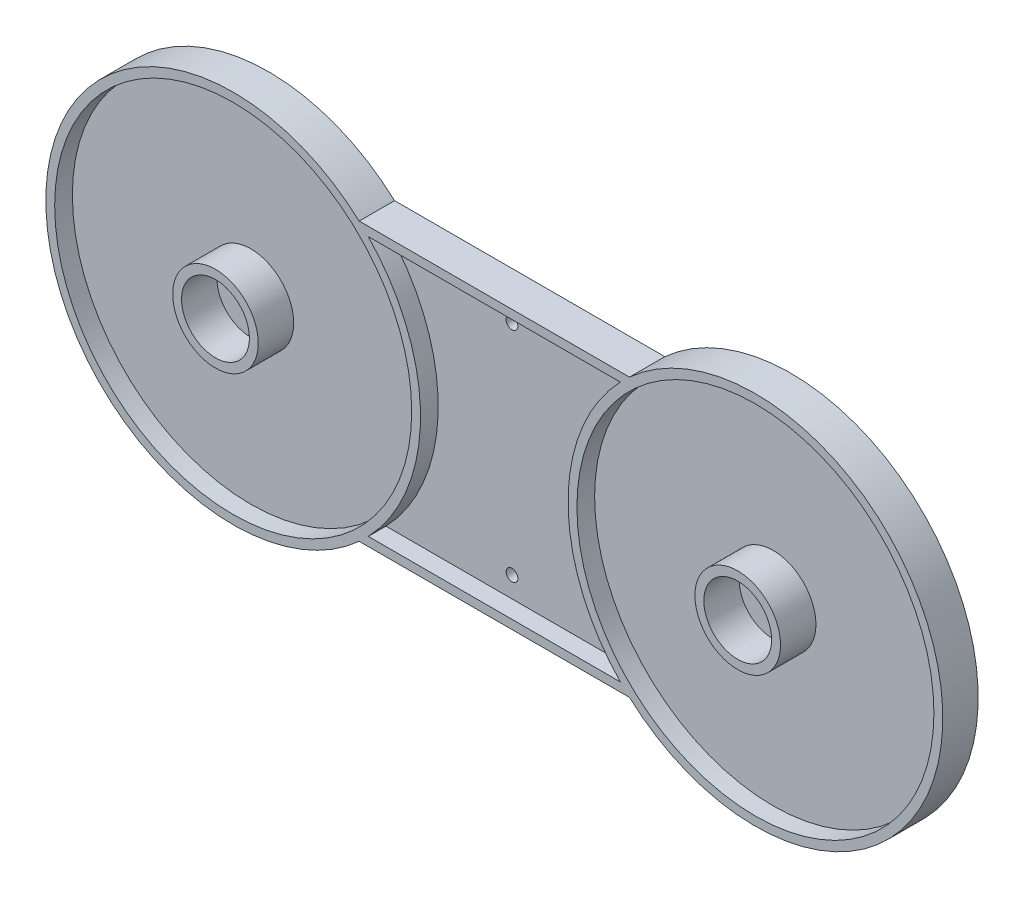
SolidWorks part; units mm, degrees
ref_plane "Ön Düzlem" through (0, 0, 0) normal (0, 0, 1) x (1, 0, 0)
ref_plane "Üst Düzlem" through (0, 0, 0) normal (0, 1, 0) x (1, 0, 0)
ref_plane "Sağ Düzlem" through (0, 0, 0) normal (1, 0, 0) x (0, 0, -1)
sketch "Çizim2" plane through (0, 0, 0) normal (0, 0, 1) x (1, 0, 0)
  line L3 (-22.9002, 23.5) -> (22.9002, 23.5)
  line L4 (-22.9002, -23.5) -> (22.9002, -23.5)
  arc A0 (-22.9002, 23.5) -> (-22.9002, -23.5) centre (-44.25, 0) ccw
  arc A1 (22.9002, -23.5) -> (22.9002, 23.5) centre (44.25, 0) ccw
  circle A2 centre (0, -18.5) radius 1
  circle A3 centre (0, 18.5) radius 1
  point P4 (0, 0)
  point P6 (0, 0)
  point P12 (0, 0)
  dimension "D4" = 2
  dimension "D5" = 5
extrude "Yükseklik-Ekstrüzyon1" add sketch "Çizim2" along normal blind 3
sketch "Çizim3" plane through (0, 0, 3) normal (0, 0, 1) x (1, 0, 0)
  line L0 (-22.9002, -23.5) -> (22.9002, -23.5) construction
  line L1 (22.9002, 23.5) -> (-22.9002, 23.5) construction
  line L2 (-22.9002, -23.5) -> (22.9002, -23.5)
  line L3 (22.9002, 23.5) -> (-22.9002, 23.5)
  line L4 (-21.3576, -22) -> (21.3576, -22)
  line L5 (21.3576, 22) -> (-21.3576, 22)
  line L6 (22.9002, 22) -> (-22.9002, 22) construction
  line L7 (-22.9002, -22) -> (22.9002, -22) construction
  circle A0 centre (-44.25, 0) radius 30.25
  circle A1 centre (-44.25, 0) radius 31.75
  circle A2 centre (44.25, 0) radius 31.75
  circle A3 centre (44.25, 0) radius 30.25
  arc M4 (22.9002, -23.5) -> (22.9002, 23.5) centre (44.25, 0) ccw
  line M5 (22.9002, 23.5) -> (-22.9002, 23.5)
  arc M6 (-22.9002, 23.5) -> (-22.9002, -23.5) centre (-44.25, 0) ccw
  line M7 (-22.9002, -23.5) -> (22.9002, -23.5)
  dimension "D1" = 60.5
  dimension "D2" = 60.5
  dimension "D4" = 63.5
  dimension "D5" = 63.5
  dimension "D3" = 1.5
extrude "Yükseklik-Ekstrüzyon2" add sketch "Çizim3" along normal blind 3 contours A1 A0 M6 | A2 A3 M4 | A2 L4 A1 M7 | A2 A1 L5 M5
sketch "Çizim4" plane through (0, 0, 3) normal (0, 0, 1) x (1, 0, 0)
  line L0 (0, 0) -> (0, 31.3571) construction
  circle A0 centre (-44.25, 0) radius 5.75
  circle A1 centre (-44.25, 0) radius 7.25
  circle A2 centre (44.25, 0) radius 7.25
  circle A3 centre (44.25, 0) radius 5.75
  dimension "D1" = 11.5
  dimension "D2" = 14.5
extrude "Yükseklik-Ekstrüzyon3" add sketch "Çizim4" along normal blind 6
